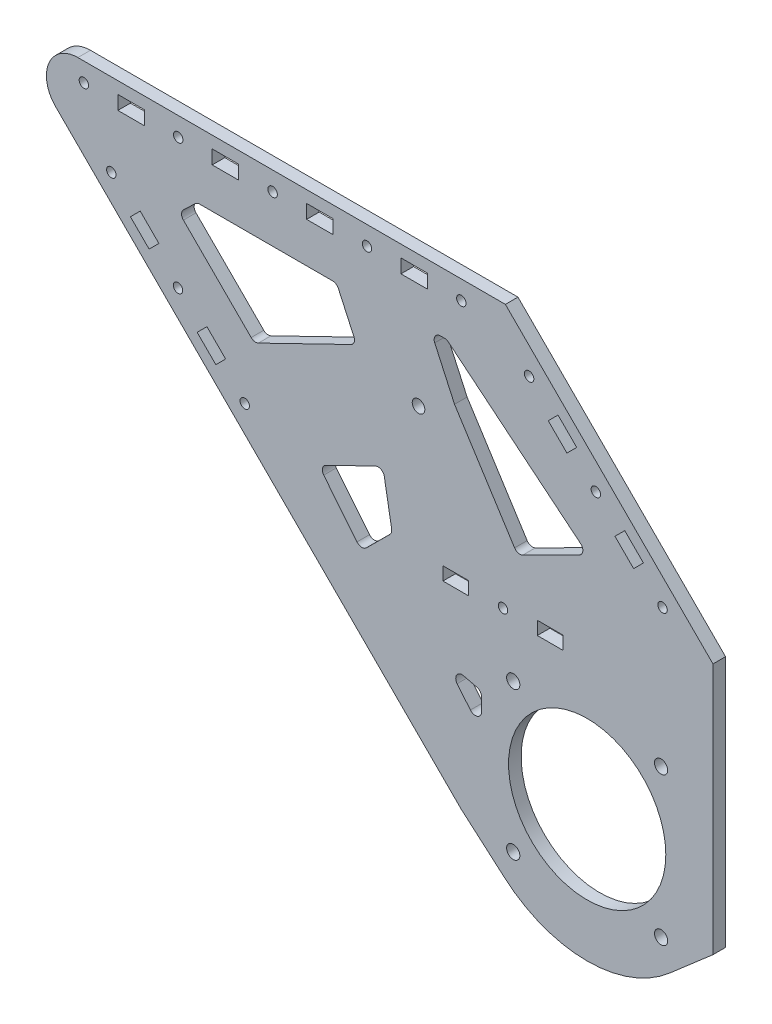
SolidWorks part; units mm, degrees
ref_plane "前视基准面" through (0, 0, 0) normal (0, 0, 1) x (1, 0, 0)
ref_plane "上视基准面" through (0, 0, 0) normal (0, 1, 0) x (1, 0, 0)
ref_plane "右视基准面" through (0, 0, 0) normal (1, 0, 0) x (0, 0, -1)
sketch "草图1" plane through (0, 0, 0) normal (0, 0, 1) x (1, 0, 0)
  line L261 (47.0274, 35.0547) -> (47.0274, 15.0547) construction
  line L315 (7.0274, -5.0025) -> (20.8108, -16.9604)
  line L316 (-52.9726, 135.0547) -> (-52.9726, 126.7057) construction
  line L332 (-112.9726, 135.0547) -> (-97.9726, 135.0547) construction
  line L334 (-42.1726, 137.2547) -> (-33.7726, 137.2547)
  line L335 (-42.1726, 137.2547) -> (-42.1726, 132.8547)
  line L336 (-42.1726, 132.8547) -> (-33.7726, 132.8547)
  line L337 (-33.7726, 137.2547) -> (-33.7726, 132.8547)
  line L338 (-42.1726, 137.2547) -> (-33.7726, 132.8547) construction
  line L339 (-42.1726, 132.8547) -> (-33.7726, 137.2547) construction
  line L389 (-114.8877, 141.0547) -> (21.0274, 141.0547)
  line L390 (-22.9726, 135.0547) -> (-22.9726, 144.5851) construction
  line L395 (-37.9726, 135.0547) -> (-7.9726, 135.0547) construction
  line L418 (87.0274, 75.0547) -> (21.0274, 141.0547)
  line L419 (-3.7726, 132.8547) -> (-12.1726, 137.2547) construction
  line L420 (-3.7726, 137.2547) -> (-12.1726, 132.8547) construction
  line L421 (7.0274, 135.0547) -> (-7.9726, 135.0547) construction
  line L422 (-12.1726, 137.2547) -> (-12.1726, 132.8547)
  line L423 (-3.7726, 132.8547) -> (-12.1726, 132.8547)
  line L424 (-3.7726, 137.2547) -> (-3.7726, 132.8547)
  line L443 (-3.7726, 137.2547) -> (-12.1726, 137.2547)
  line L444 (-102.1726, 137.2547) -> (-93.7726, 132.8547) construction
  line L445 (-102.1726, 132.8547) -> (-93.7726, 137.2547) construction
  line L446 (7.0274, -5.0025) -> (-139.0298, 141.0547) construction
  line L447 (-67.9726, 135.0547) -> (-97.9726, 135.0547) construction
  line L449 (-63.7726, 132.8547) -> (-72.1726, 137.2547) construction
  line L483 (-63.7726, 137.2547) -> (-72.1726, 132.8547) construction
  line L515 (47.0274, 35.0547) -> (47.0274, 135.0547) construction
  line L516 (47.0274, 135.0547) -> (-52.9726, 135.0547) construction
  line L517 (-102.1726, 137.2547) -> (-93.7726, 137.2547)
  line L518 (-102.1726, 137.2547) -> (-102.1726, 132.8547)
  line L519 (-102.1726, 132.8547) -> (-93.7726, 132.8547)
  line L520 (-93.7726, 137.2547) -> (-93.7726, 132.8547)
  line L521 (-72.1726, 137.2547) -> (-72.1726, 132.8547)
  line L522 (-63.7726, 132.8547) -> (-72.1726, 132.8547)
  line L523 (-63.7726, 137.2547) -> (-63.7726, 132.8547)
  line L524 (-63.7726, 137.2547) -> (-72.1726, 137.2547)
  line L551 (7.0274, -5.0025) -> (87.0274, -5.0025) construction
  line L552 (7.0274, -5.0025) -> (7.0274, 75.0547) construction
  line L553 (7.0274, 75.0547) -> (87.0274, 75.0547) construction
  line L554 (87.0274, -5.0025) -> (87.0274, 75.0547)
  line L556 (21.4033, 132.1936) -> (81.3921, 72.2048) construction
  line L557 (54.0274, 108.0547) -> (35.0674, 89.0947) construction
  line L558 (43.7037, 113.0045) -> (34.6527, 115.8329) construction
  line L559 (55.8659, 94.6197) -> (61.8056, 88.68)
  line L576 (55.8659, 94.6197) -> (58.9772, 97.731)
  line L577 (58.9772, 97.731) -> (64.9169, 91.7913)
  line L578 (61.8056, 88.68) -> (64.9169, 91.7913)
  line L579 (55.8659, 94.6197) -> (64.9169, 91.7913) construction
  line L580 (58.9772, 97.731) -> (61.8056, 88.68) construction
  line L581 (40.5924, 109.8932) -> (37.764, 118.9442) construction
  line L582 (34.6527, 115.8329) -> (37.764, 118.9442)
  line L583 (43.7037, 113.0045) -> (37.764, 118.9442)
  line L584 (40.5924, 109.8932) -> (43.7037, 113.0045)
  line L585 (40.5924, 109.8932) -> (34.6527, 115.8329)
  line L586 (60.3914, 93.2055) -> (58.8358, 91.6499) construction
  line L587 (39.1782, 114.4187) -> (37.6226, 112.8631) construction
  line L589 (20.2758, 57.0547) -> (5.2758, 57.0547) construction
  line L594 (73.2276, -16.9678) -> (87.0274, -5.0025)
  line L599 (-90.2039, 92.2289) -> (-121.9587, 123.9837)
  line L600 (-73.8521, 87.4736) -> (-76.9634, 84.3624)
  line L605 (-25.9726, 27.9975) -> (-21.7299, 32.2402) construction
  line L607 (-83.0445, 93.5547) -> (-87.2872, 89.3121) construction
  line L608 (-90.2039, 92.2289) -> (7.0274, -5.0025)
  line L621 (-83.0445, 93.5547) -> (-61.8313, 72.3415) construction
  line L622 (-73.8521, 87.4736) -> (-67.9124, 81.5339)
  line L623 (47.0274, 15.0547) -> (89.2922, -52.8694) construction
  line L624 (23.5274, -8.4453) -> (70.5274, -8.4453) construction
  line L625 (-76.9634, 84.3624) -> (-71.0237, 78.4227)
  line L630 (-67.9124, 81.5339) -> (-71.0237, 78.4227)
  line L631 (-73.8521, 87.4736) -> (-71.0237, 78.4227) construction
  line L632 (-82.9726, 135.0547) -> (-82.9726, 64.2144) construction
  line L633 (-76.9634, 84.3624) -> (-67.9124, 81.5339) construction
  line L634 (-89.1256, 102.7471) -> (-92.2369, 99.6359)
  line L635 (-92.2369, 99.6359) -> (-98.1766, 105.5756)
  line L636 (-95.0653, 108.6868) -> (-98.1766, 105.5756)
  line L637 (-89.1256, 102.7471) -> (-95.0653, 108.6868)
  line L638 (-22.9726, 135.0547) -> (-22.9726, 124.9547) construction
  line L639 (-22.9726, 124.9547) -> (47.0274, 15.0547) construction
  line L640 (20.2758, 57.0547) -> (20.2758, 57.6954) construction
  line L641 (9.3758, 54.9547) -> (1.1758, 54.9547)
  line L642 (9.3758, 54.9547) -> (9.3758, 59.1547)
  line L643 (9.3758, 59.1547) -> (1.1758, 59.1547)
  line L644 (1.1758, 54.9547) -> (1.1758, 59.1547)
  line L645 (9.3758, 54.9547) -> (1.1758, 59.1547) construction
  line L646 (9.3758, 59.1547) -> (1.1758, 54.9547) construction
  line L647 (31.1758, 59.1547) -> (39.3758, 54.9547) construction
  line L648 (31.1758, 54.9547) -> (39.3758, 59.1547) construction
  line L649 (39.3758, 54.9547) -> (39.3758, 59.1547)
  line L650 (31.1758, 59.1547) -> (39.3758, 59.1547)
  line L651 (31.1758, 54.9547) -> (31.1758, 59.1547)
  line L652 (31.1758, 54.9547) -> (39.3758, 54.9547)
  line L653 (-6.5853, 99.2267) -> (-61.8313, 72.3415) construction
  line L654 (-104.2577, 114.7679) -> (-82.9726, 135.0547) construction
  line L655 (-82.9726, 135.0547) -> (-22.9726, 135.0547) construction
  line L656 (-22.9726, 135.0547) -> (-6.5853, 99.2267) construction
  line L657 (-61.8313, 72.3415) -> (-104.2577, 114.7679) construction
  line L658 (-26.3178, 106.3059) -> (-58.7833, 90.5067)
  line L659 (-58.7833, 90.5067) -> (-82.7867, 114.5102)
  line L660 (-82.7867, 114.5102) -> (-76.9693, 120.0547)
  line L661 (-76.9693, 120.0547) -> (-32.6063, 120.0547)
  line L662 (-32.6063, 120.0547) -> (-26.3178, 106.3059)
  line L663 (70.998, 82.5989) -> (20.2758, 57.0547) construction
  line L664 (70.998, 82.5989) -> (7.0274, 135.0547) construction
  line L665 (7.0274, 135.0547) -> (-22.9726, 135.0547) construction
  line L666 (-6.5853, 99.2267) -> (20.2758, 57.0547) construction
  line L667 (47.2997, 85.2197) -> (24.9262, 73.9522)
  line L668 (4.8626, 105.452) -> (24.9262, 73.9522)
  line L669 (-2.7313, 122.0547) -> (4.8626, 105.452)
  line L670 (2.3789, 122.0547) -> (-2.7313, 122.0547)
  line L671 (47.2997, 85.2197) -> (2.3789, 122.0547)
  line L672 (1.1758, 54.9547) -> (-6.5853, 99.2267) construction
  line L673 (-61.8313, 72.3415) -> (-25.9726, 27.9975) construction
  line L674 (-25.9726, 27.9975) -> (1.1758, 54.9547) construction
  line L675 (-14.9514, 60.0798) -> (-17.9224, 77.0277)
  line L676 (-17.9224, 77.0277) -> (-38.3079, 67.1072)
  line L677 (-38.3079, 67.1072) -> (-24.754, 50.3461)
  line L678 (-24.754, 50.3461) -> (-14.9514, 60.0798)
  line L679 (23.4574, -8.5153) -> (23.4574, 38.6247) construction
  line L680 (23.4574, 38.6247) -> (-24.754, 50.3461) construction
  line L681 (-24.754, 50.3461) -> (23.4574, -8.5153) construction
  line L682 (1.9115, 33.5718) -> (13.4574, 19.4754)
  line L683 (13.4574, 19.4754) -> (13.4574, 30.7647)
  line L684 (13.4574, 30.7647) -> (1.9115, 33.5718)
  line L685 (23.5274, -8.4453) -> (23.5274, 38.5547) construction
  line L686 (23.5274, 38.5547) -> (70.5274, 38.5547) construction
  line L687 (70.5274, -8.4453) -> (70.5274, 38.5547) construction
  line L688 (23.5274, -8.4453) -> (70.5274, 38.5547) construction
  line L689 (23.5274, 38.5547) -> (70.5274, -8.4453) construction
  circle A39 centre (-52.9726, 135.0547) radius 1.5
  circle A42 centre (47.0274, 15.0547) radius 25
  circle A49 centre (-22.9726, 135.0547) radius 1.5
  circle A69 centre (7.0274, 135.0547) radius 1.5
  circle A92 centre (-112.9726, 135.0547) radius 1.5
  circle A93 centre (-82.9726, 135.0547) radius 1.5
  circle A98 centre (49.7848, 103.8121) radius 1.5
  circle A99 centre (70.998, 82.5989) radius 1.5
  circle A100 centre (28.5716, 125.0253) radius 1.5
  arc A111 (73.2276, -16.9678) -> (20.8108, -16.9604) centre (47.0235, 13.2537) cw
  arc A115 (-114.8877, 141.0547) -> (-121.9587, 123.9837) centre (-114.8877, 131.0547) ccw
  circle A116 centre (-83.0445, 93.5547) radius 1.5
  circle A117 centre (-61.8313, 72.3415) radius 1.5
  circle A118 centre (-104.2577, 114.7679) radius 1.5
  circle A121 centre (20.2758, 57.0547) radius 1.5
  circle A122 centre (-6.5853, 99.2267) radius 2
  circle A123 centre (70.5274, -8.4453) radius 2.1
  circle A124 centre (23.5274, -8.4453) radius 2.1
  circle A125 centre (23.5274, 38.5547) radius 2.1
  circle A126 centre (70.5274, 38.5547) radius 2.1
  point P5 (210.9534, 218.4629)
  point P6 (288.6284, 218.4629)
  point P54 (-105.4726, 135.0547)
  point P60 (60.3914, 93.2055)
  point P88 (-72.4379, 82.9481)
  point P115 (47.016, -39.6951)
  dimension "D1" = 40
  dimension "D3" = 50
  dimension "D5" = 4
  dimension "D4" = 47
  dimension "D2" = 40
  dimension "D7" = 6
  dimension "D12" = 3
  dimension "D22" = 3
  dimension "D8" = 30
  dimension "D28" = 40
  dimension "D26" = 10
  dimension "D17" = 10.1
  dimension "D29" = 42
  dimension "D30" = 50
  dimension "D31" = 15
  dimension "D9" = 15
  dimension "D10" = 15
  dimension "D11" = 8.4
  dimension "D13" = 4.4
  dimension "D14" = 6
  dimension "D15" = 45
  dimension "D16" = 41.5
  dimension "D21" = 6
  dimension "D23" = 15
  dimension "D24" = 8.4
  dimension "D25" = 4.4
  dimension "D32" = 8.2
  dimension "D33" = 4.2
  dimension "D34" = 120
  dimension "D35" = 70
  dimension "D36" = 15
  dimension "D37" = 13
  dimension "D38" = 15
  dimension "D39" = 10
extrude "凸台-拉伸1" add sketch "草图1" along normal blind 4
sketch "草图2" plane through (0, 0, 4) normal (0, 0, 1) x (1, 0, 0)
  line L0 (47.0274, 15.0547) -> (-6.5853, 99.2267)
  line L1 (-6.5853, 99.2267) -> (-33.2273, 141.0547)
  line L2 (21.0274, 141.0547) -> (-114.8877, 141.0547) construction
  line L3 (-22.9726, 135.0547) -> (-22.9726, 124.9547)
  line L5 (39.3758, 54.9547) -> (31.1758, 54.9547)
  line L6 (39.3758, 54.9547) -> (39.3758, 59.1547)
  line L7 (39.3758, 59.1547) -> (31.1758, 59.1547)
  line L8 (31.1758, 54.9547) -> (31.1758, 59.1547)
  line L13 (-33.7726, 132.8547) -> (-42.1726, 132.8547)
  line L14 (-33.7726, 132.8547) -> (-33.7726, 137.2547)
  line L15 (-33.7726, 137.2547) -> (-42.1726, 137.2547)
  line L16 (-42.1726, 132.8547) -> (-42.1726, 137.2547)
  line L17 (9.3758, 54.9547) -> (1.1758, 54.9547)
  line L18 (9.3758, 54.9547) -> (9.3758, 59.1547)
  line L19 (9.3758, 59.1547) -> (1.1758, 59.1547)
  line L20 (1.1758, 54.9547) -> (1.1758, 59.1547)
  circle A1 centre (-22.9726, 135.0547) radius 1.5
  circle A2 centre (-6.5853, 99.2267) radius 2
  circle A3 centre (20.2758, 57.0547) radius 1.5
  circle A4 centre (47.0274, 15.0547) radius 22.5
fillet "圆角2" radius 2 16 edges at (-76.9693, 120.0547, 2) (-82.7867, 114.5102, 2) (-32.6063, 120.0547, 2) (-26.3178, 106.3059, 2) (-58.7833, 90.5067, 2) (-17.9224, 77.0277, 2) (-14.9514, 60.0798, 2) (-24.754, 50.3461, 2) (-38.3079, 67.1072, 2) (47.2997, 85.2197, 2) (24.9262, 73.9522, 2) (2.3789, 122.0547, 2) (-2.7313, 122.0547, 2) (13.4574, 30.7647, 2) (1.9115, 33.5718, 2) (13.4574, 19.4754, 2)
